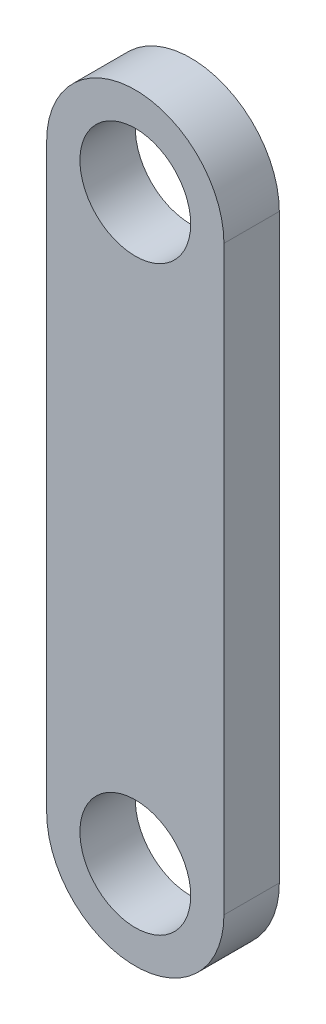
SolidWorks part; units mm, degrees
ref_plane "前基準面" through (0, 0, 0) normal (0, 0, 1) x (1, 0, 0)
ref_plane "上基準面" through (0, 0, 0) normal (0, 1, 0) x (1, 0, 0)
ref_plane "右基準面" through (0, 0, 0) normal (1, 0, 0) x (0, 0, -1)
sketch "草圖1" plane through (0, 0, 0) normal (0, 0, 1) x (1, 0, 0)
  line L0 (0, -2.625) -> (0, 2.625) construction
  line L1 (-0.8, -2.625) -> (-0.8, 2.625)
  line L2 (0.8, -2.625) -> (0.8, 2.625)
  arc A0 (-0.8, -2.625) -> (0.8, -2.625) centre (0, -2.625) ccw
  arc A1 (0.8, 2.625) -> (-0.8, 2.625) centre (0, 2.625) ccw
  circle A2 centre (0, 2.625) radius 0.5
  circle A3 centre (0, -2.625) radius 0.5
  point P2 (0, 0)
  dimension "D1" = 1
  dimension "D2" = 0.8
  dimension "D4" = 1
  dimension "D3" = 5.25
extrude "填料-伸長1" add sketch "草圖1" along normal blind 0.5
